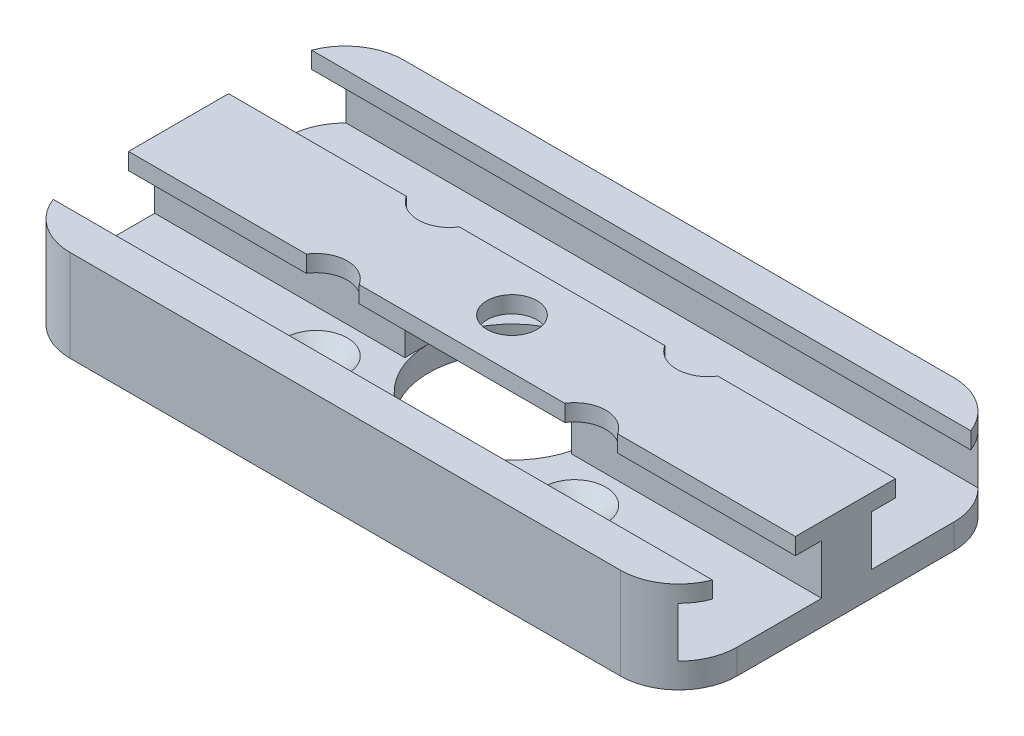
SolidWorks part; units mm, degrees
ref_plane "Front Plane" through (0, 0, 0) normal (0, 0, 1) x (1, 0, 0)
ref_plane "Top Plane" through (0, 0, 0) normal (0, 1, 0) x (1, 0, 0)
ref_plane "Right Plane" through (0, 0, 0) normal (1, 0, 0) x (0, 0, -1)
sketch "Sketch1" plane through (0, 0, 0) normal (0, 1, 0) x (1, 0, 0)
  line L1 (40, 20) -> (-40, 20)
  line L2 (40, 20) -> (40, -20)
  line L3 (40, -20) -> (-40, -20)
  line L4 (-40, 20) -> (-40, -20)
  line L5 (40, 20) -> (-40, -20) construction
  line L6 (40, -20) -> (-40, 20) construction
  circle A0 centre (0, 0) radius 10
  point P0 (0, 0)
  dimension "D1" = 80
  dimension "D2" = 40
extrude "Boss-Extrude1" add sketch "Sketch1" along normal blind 3
sketch "Sketch2" plane through (0, 3, 0) normal (0, 1, 0) x (1, 0, 0)
  line L1 (40, -20) -> (40, 20) construction
  line L2 (-40, 20) -> (40, 20)
  line L3 (-40, 20) -> (-40, 15.5)
  line L4 (-40, 15.5) -> (40, 15.5)
  line L5 (40, 20) -> (40, 15.5)
  line L7 (-40, -20) -> (40, -20)
  line L8 (-40, -20) -> (-40, -15.5)
  line L9 (-40, -15.5) -> (40, -15.5)
  line L10 (40, -20) -> (40, -15.5)
  point P12 (0, 0)
  dimension "D1" = 4.5
  dimension "D2" = 4.5
extrude "Boss-Extrude2" add sketch "Sketch2" along normal blind 8
sketch "Sketch3" plane through (-40, 0, 0) normal (-1, 0, 0) x (0, 0, 1)
  line L1 (-15.5, 3) -> (-18, 3)
  line L2 (-15.5, 3) -> (-15.5, 9)
  line L3 (-15.5, 9) -> (-18, 9)
  line L4 (-18, 3) -> (-18, 9)
  line L5 (15.5, 3) -> (18, 3)
  line L6 (15.5, 3) -> (15.5, 9)
  line L7 (15.5, 9) -> (18, 9)
  line L8 (18, 3) -> (18, 9)
  dimension "D1" = 2.5
  dimension "D2" = 6
  dimension "D3" = 2.5
  dimension "D4" = 6
extrude "Cut-Extrude1" cut sketch "Sketch3" against normal blind 80
sketch "Sketch4" plane through (0, 3, 0) normal (0, 1, 0) x (1, 0, 0)
  line L0 (40, 20) -> (-40, 20) construction
  line L1 (40, -18) -> (40, 18) construction
  line L2 (-40, 18) -> (-40, -18) construction
  line L3 (-40, -20) -> (40, -20) construction
  circle A0 centre (-15.5, 8) radius 3.75
  circle A1 centre (-15.5, -8) radius 3.75
  circle A3 centre (15.5, -8) radius 3.75
  circle A4 centre (15.5, 8) radius 3.75
  point P0 (0, 0)
  point P2 (-26.0236, 18.2815)
  dimension "D1" = 7.5
  dimension "D2" = 7.5
  dimension "D3" = 16
  dimension "D4" = 31
  dimension "D5" = 12
  dimension "D6" = 12
  dimension "D7" = 31
  dimension "D8" = 16
  dimension "D9" = 12
  dimension "D10" = 12
  dimension "D11" = 24.5
  dimension "D12" = 24.5
  dimension "D13" = 15.5
sketch "Sketch5" plane through (0, 0, 0) normal (0, -1, 0) x (1, 0, 0)
  circle A0 centre (-15.5, 8) radius 1.75
  circle A1 centre (-15.5, -8) radius 1.75
  circle A2 centre (15.5, 8) radius 1.75
  circle A3 centre (15.5, -8) radius 1.75
extrude "Cut-Extrude3" cut sketch "Sketch5" against normal blind 1
extrude "Cut-Extrude4" cut sketch "Sketch4" against normal blind 2 draft 45
fillet "Fillet1" radius 7 4 edges at (40, 5.5, 20) (40, 5.5, -20) (-40, 5.5, 20) (-40, 5.5, -20)
sketch "Sketch6" plane through (0, 3, 0) normal (0, 1, 0) x (1, 0, 0)
  line L0 (-40, 3.1453) -> (-40, -2.8547)
  line L1 (-40, 13) -> (-40, -13) construction
  line L2 (-40, -2.8547) -> (-10, -2.8547)
  line L3 (-10, -2.8547) -> (-10, 3.1453)
  line L4 (-10, 3.1453) -> (-40, 3.1453)
  line L5 (0, 0) -> (-40, 0.1453) construction
  line L6 (0, 0) -> (0, -10) construction
  line L7 (10, -2.8547) -> (10, 3.1453)
  line L8 (40, -2.8547) -> (10, -2.8547)
  line L9 (40, 3.1453) -> (40, -2.8547)
  line L10 (10, 3.1453) -> (40, 3.1453)
  circle A0 centre (0, 0) radius 10 construction
  dimension "D1" = 6
  dimension "D2" = 30
  dimension "D3" = 3
extrude "Boss-Extrude3" add sketch "Sketch6" along normal blind 6
sketch "Sketch7" plane through (0, 9, 0) normal (0, 1, 0) x (1, 0, 0)
  line L0 (-40, -2.8547) -> (-40, -13) construction
  line L1 (40, 6) -> (18.6721, 6)
  line L2 (40, 6) -> (40, -6)
  line L3 (40, -6) -> (18.6721, -6)
  line L4 (-40, 6) -> (-40, -6)
  line L7 (-40, 0) -> (40, 0) construction
  line L8 (0, 6) -> (0, -6) construction
  line L9 (-18.6721, 6) -> (-40, 6)
  line L10 (-18.6721, -6) -> (-40, -6)
  line L11 (12.3279, -6) -> (-12.3279, -6)
  line L12 (12.3279, 6) -> (-12.3279, 6)
  arc A0 (-18.6721, 6) -> (-12.3279, 6) centre (-15.5, 8) ccw
  arc A1 (-18.6721, -6) -> (-12.3279, -6) centre (-15.5, -8) cw
  arc A2 (18.6721, -6) -> (12.3279, -6) centre (15.5, -8) ccw
  arc A3 (18.6721, 6) -> (12.3279, 6) centre (15.5, 8) cw
  circle A4 centre (0, 0) radius 3
  point P0 (0, 0)
  dimension "D1" = 12
extrude "Boss-Extrude4" add sketch "Sketch7" along normal blind 2
equation "\"D3@Cut-Extrude4\"=arccotan( 45)"
